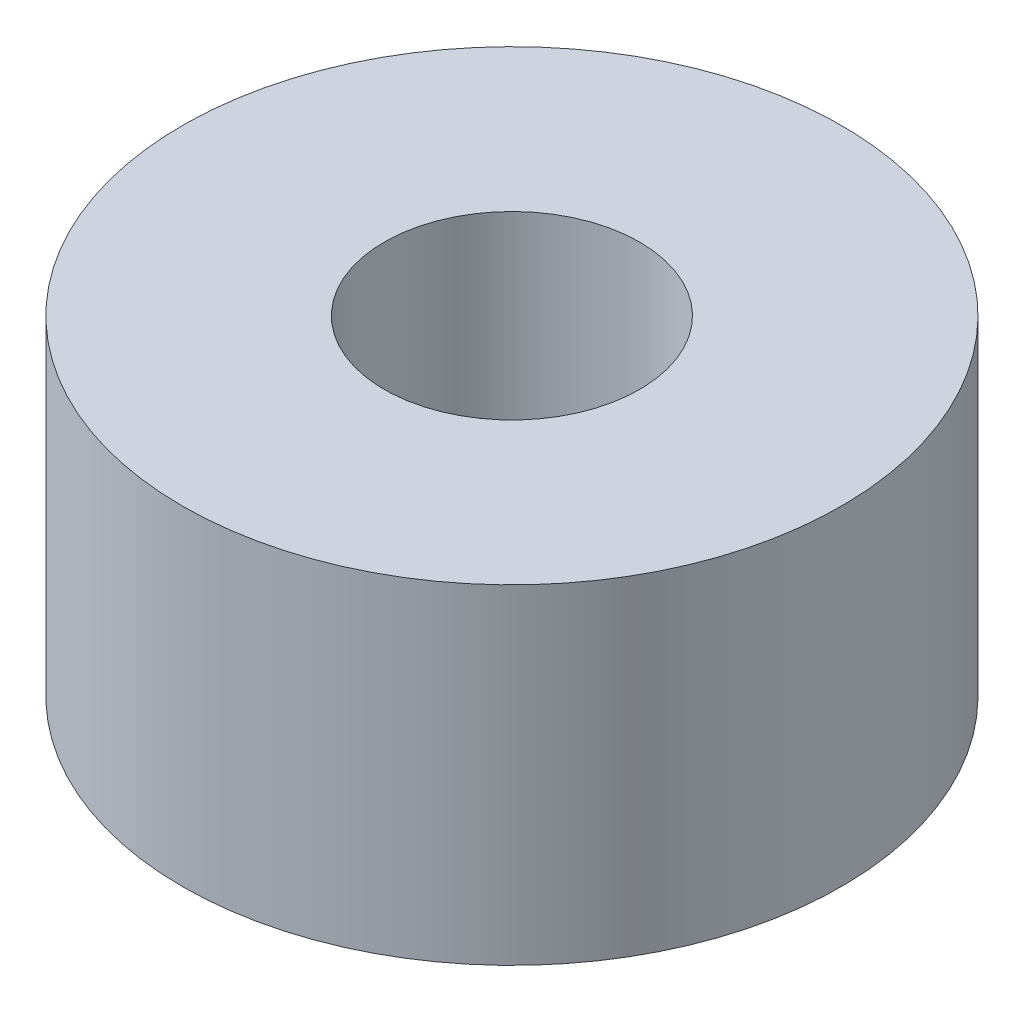
SolidWorks part; units mm, degrees
ref_plane "Front Plane" through (0, 0, 0) normal (0, 0, 1) x (1, 0, 0)
ref_plane "Top Plane" through (0, 0, 0) normal (0, 1, 0) x (1, 0, 0)
ref_plane "Right Plane" through (0, 0, 0) normal (1, 0, 0) x (0, 0, -1)
sketch "Sketch1" plane through (0, 0, 0) normal (0, 1, 0) x (1, 0, 0)
  circle A0 centre (0, 0) radius 4
  dimension "D1" = 8
extrude "Boss-Extrude1" add sketch "Sketch1" along normal blind 4
hole_wizard "M2.5 Clearance Hole1" positions "Sketch2" profile "Sketch3" hole size "M2.5" standard "ANSI Metric" end condition through all
sketch "Sketch2" plane through (0, 0, 0) normal (0, -1, 0) x (-1, 0, 0)
  point P0 (0, 0)
sketch "Sketch3" plane through (0, 0, 0) normal (1, 0, 0) x (0, 0, -1)
  line L0 (0, 0) -> (0, 4)
  line L1 (0, 4) -> (1.55, 4)
  line L2 (1.55, 4) -> (1.55, 0)
  line L5 (1.55, 0) -> (0, 0)
  line L11 (0, -6.35) -> (0, 107.95) construction
  dimension "Thru Hole Dia." = 3.1
  dimension "Thru Hole Depth" = 4
